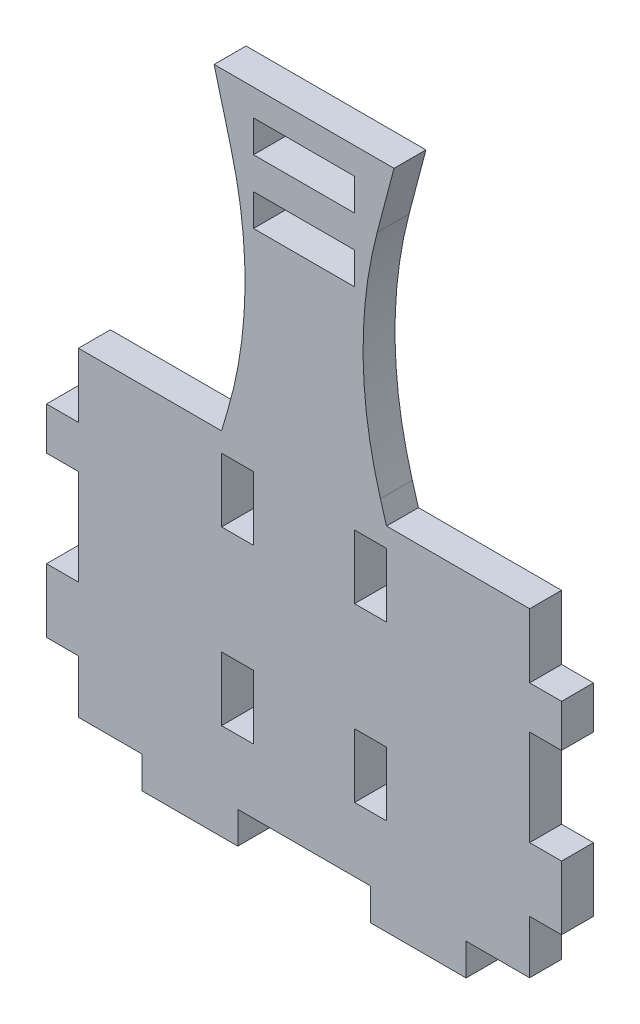
SolidWorks part; units mm, degrees
ref_plane "Front Plane" through (0, 0, 0) normal (0, 0, 1) x (1, 0, 0)
ref_plane "Top Plane" through (0, 0, 0) normal (0, 1, 0) x (1, 0, 0)
ref_plane "Right Plane" through (0, 0, 0) normal (1, 0, 0) x (0, 0, -1)
sketch "Sketch1" plane through (0, 0, 0) normal (0, 0, 1) x (1, 0, 0)
  line L0 (-71.0095, -30.9235) -> (-71.0095, -48.9235)
  line L1 (-71.0095, -10.8515) -> (-44.1124, -10.8515)
  line L2 (-71.0095, -10.8515) -> (-71.0095, -22.9235)
  line L3 (-71.0095, -70.9235) -> (-59.0695, -70.9235)
  line L4 (13.7847, -10.8515) -> (13.7847, -22.9235)
  line L5 (13.7847, -22.9235) -> (19.7847, -22.9235)
  line L6 (-38.1124, -46.8306) -> (-19.1124, -46.8306) construction
  line L7 (13.7847, -30.9235) -> (19.7847, -30.9235)
  line L8 (19.7847, -22.9235) -> (19.7847, -30.9235)
  line L9 (13.7847, -48.9235) -> (19.7847, -48.9235)
  line L10 (13.7847, -30.9235) -> (13.7847, -48.9235)
  line L11 (13.7847, -60.9235) -> (19.7847, -60.9235)
  line L12 (19.7847, -48.9235) -> (19.7847, -60.9235)
  line L13 (13.7847, -60.9235) -> (13.7847, -70.9235)
  line L14 (-16.1553, -70.9235) -> (-16.1553, -76.9235)
  line L15 (-16.1553, -76.9235) -> (1.8447, -76.9235)
  line L16 (1.8447, -70.9235) -> (1.8447, -76.9235)
  line L17 (1.8447, -70.9235) -> (13.7847, -70.9235)
  line L18 (-59.0695, -70.9235) -> (-59.0695, -76.9235)
  line L19 (-59.0695, -76.9235) -> (-41.0695, -76.9235)
  line L20 (-41.0695, -70.9235) -> (-41.0695, -76.9235)
  line L21 (-77.0095, -60.9235) -> (-71.0095, -60.9235)
  line L22 (-77.0095, -60.9235) -> (-77.0095, -48.9235)
  line L23 (-77.0095, -48.9235) -> (-71.0095, -48.9235)
  line L24 (-41.0695, -70.9235) -> (-16.1553, -70.9235)
  line L25 (-77.0095, -30.9235) -> (-71.0095, -30.9235)
  line L26 (-77.0095, -30.9235) -> (-77.0095, -22.9235)
  line L27 (-77.0095, -22.9235) -> (-71.0095, -22.9235)
  line L28 (-71.0095, -60.9235) -> (-71.0095, -70.9235)
  line L29 (-44.1124, -46.8306) -> (-38.1124, -46.8306)
  line L30 (-44.1124, -46.8306) -> (-44.1124, -58.8306)
  line L31 (-44.1124, -58.8306) -> (-38.1124, -58.8306)
  line L32 (-38.1124, -46.8306) -> (-38.1124, -58.8306)
  line L33 (-44.1124, -26.4845) -> (-38.1124, -26.4845)
  line L34 (-44.1124, -26.4845) -> (-44.1124, -14.4845)
  line L35 (-44.1124, -14.4845) -> (-38.1124, -14.4845)
  line L36 (-38.1124, -26.4845) -> (-38.1124, -14.4845)
  line L37 (-19.1124, -26.4845) -> (-13.1124, -26.4845)
  line L38 (-19.1124, -26.4845) -> (-19.1124, -14.4845)
  line L39 (-19.1124, -14.4845) -> (-13.1124, -14.4845)
  line L40 (-13.1124, -26.4845) -> (-13.1124, -14.4845)
  line L41 (-19.1124, -46.8306) -> (-13.1124, -46.8306)
  line L42 (-19.1124, -46.8306) -> (-19.1124, -58.8306)
  line L43 (-19.1124, -58.8306) -> (-13.1124, -58.8306)
  line L44 (-13.1124, -46.8306) -> (-13.1124, -58.8306)
  line L45 (-28.6124, -46.8306) -> (-28.6124, -70.9235) construction
  line L46 (-44.1124, -10.8515) -> (-42.9668, -6.9674)
  line L47 (-42.3388, 36.0459) -> (-45.5107, 48.0852)
  line L48 (-45.5107, 48.0852) -> (-11.7015, 48.0852)
  line L49 (-11.7015, 48.0852) -> (-14.876, 36.0466)
  line L50 (-14.2571, -6.9672) -> (-13.1124, -10.8515)
  line L51 (-13.1124, -10.8515) -> (13.7847, -10.8515)
  line L52 (-38.1124, 43.0852) -> (-38.1124, 48.0852) construction
  line L53 (-38.1124, 43.0852) -> (-19.0998, 43.0852)
  line L54 (-38.1124, 43.0852) -> (-38.1124, 37.0852)
  line L55 (-38.1124, 37.0852) -> (-19.0998, 37.0852)
  line L56 (-19.0998, 43.0852) -> (-19.0998, 37.0852)
  line L57 (-38.1124, 31.0852) -> (-19.0998, 31.0852)
  line L58 (-38.1124, 31.0852) -> (-38.1124, 25.0852)
  line L59 (-38.1124, 25.0852) -> (-19.0998, 25.0852)
  line L60 (-19.0998, 31.0852) -> (-19.0998, 25.0852)
  line L61 (-38.1124, 37.0852) -> (-38.1124, 31.0852) construction
  line L62 (-16.1553, -70.9235) -> (-16.1553, 48.0852) construction
  arc A0 (-42.9668, -6.9674) -> (-42.3388, 36.0459) centre (-119.6989, 15.6642) ccw
  arc A1 (-14.876, 36.0466) -> (-14.2571, -6.9672) centre (62.4797, 15.6482) ccw
  point P66 (-28.6061, 43.0852)
  point P67 (-28.6061, 48.0852)
  dimension "D1" = 80
extrude "Boss-Extrude1" add sketch "Sketch1" along normal blind 6
